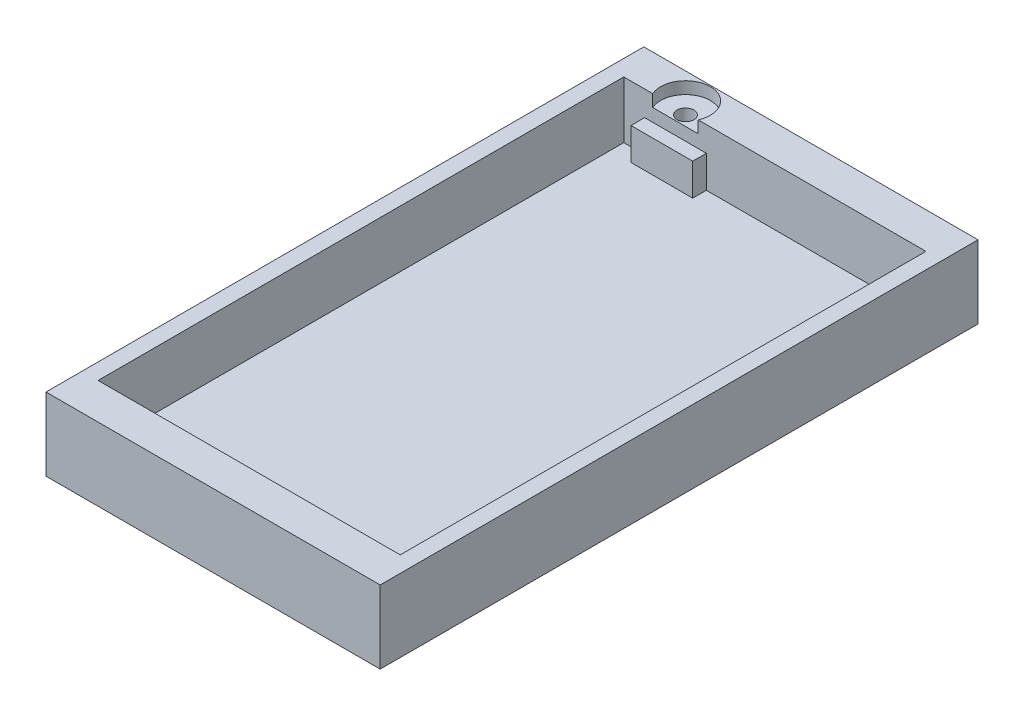
SolidWorks part; units mm, degrees
ref_plane "Front Plane" through (0, 0, 0) normal (0, 0, 1) x (1, 0, 0)
ref_plane "Top Plane" through (0, 0, 0) normal (0, 1, 0) x (1, 0, 0)
ref_plane "Right Plane" through (0, 0, 0) normal (1, 0, 0) x (0, 0, -1)
other "Configuration Table"
sketch "Sketch1" plane through (0, 0, 0) normal (0, 1, 0) x (1, 0, 0)
  line L1 (-20.85, 37.3) -> (20.85, 37.3)
  line L2 (-20.85, 37.3) -> (-20.85, -37.3)
  line L3 (-20.85, -37.3) -> (20.85, -37.3)
  line L4 (20.85, 37.3) -> (20.85, -37.3)
extrude "Boss-Extrude1" add sketch "Sketch1" along normal blind 3.1 and the other way blind 6
sketch "Sketch2" plane through (0, 0, 0) normal (0, 1, 0) x (1, 0, 0)
  line L1 (-18.85, 32.8) -> (18.85, 32.8)
  line L2 (-18.85, 32.8) -> (-18.85, -32.8)
  line L3 (-18.85, -32.8) -> (18.85, -32.8)
  line L4 (18.85, 32.8) -> (18.85, -32.8)
extrude "Cut-Extrude1" cut sketch "Sketch2" against normal blind 4 and the other way through all
sketch "Sketch3" plane through (0, 0, 0) normal (0, 1, 0) x (1, 0, 0)
  line L1 (-18.4, -32.8) -> (18.4, -32.8)
  line L2 (-18.4, -32.8) -> (-18.4, -34.8)
  line L3 (-18.4, -34.8) -> (18.4, -34.8)
  line L4 (18.4, -32.8) -> (18.4, -34.8)
extrude "Cut-Extrude2" cut sketch "Sketch3" against normal blind 0.15 and the other way blind 1.75
sketch "Sketch4" plane through (0, 0, 0) normal (0, 1, 0) x (1, 0, 0)
  line L1 (-16.25, 32.8) -> (-8.55, 32.8)
  line L2 (-16.25, 32.8) -> (-16.25, 31.1)
  line L3 (-16.25, 31.1) -> (-8.55, 31.1)
  line L4 (-8.55, 32.8) -> (-8.55, 31.1)
extrude "Boss-Extrude2" add sketch "Sketch4" against normal blind 4
sketch "Sketch5" plane through (0, 0, 0) normal (0, 1, 0) x (1, 0, 0)
  circle A0 centre (-12.4, 34.05) radius 3.1
extrude "Cut-Extrude3" cut sketch "Sketch5" along normal through all from offset 1.6
sketch "Sketch6" plane through (0, 0, 0) normal (0, 1, 0) x (1, 0, 0)
  circle A0 centre (-12.4, 34.05) radius 1.05
extrude "Cut-Extrude4" cut sketch "Sketch6" against normal blind 5 and the other way through all
